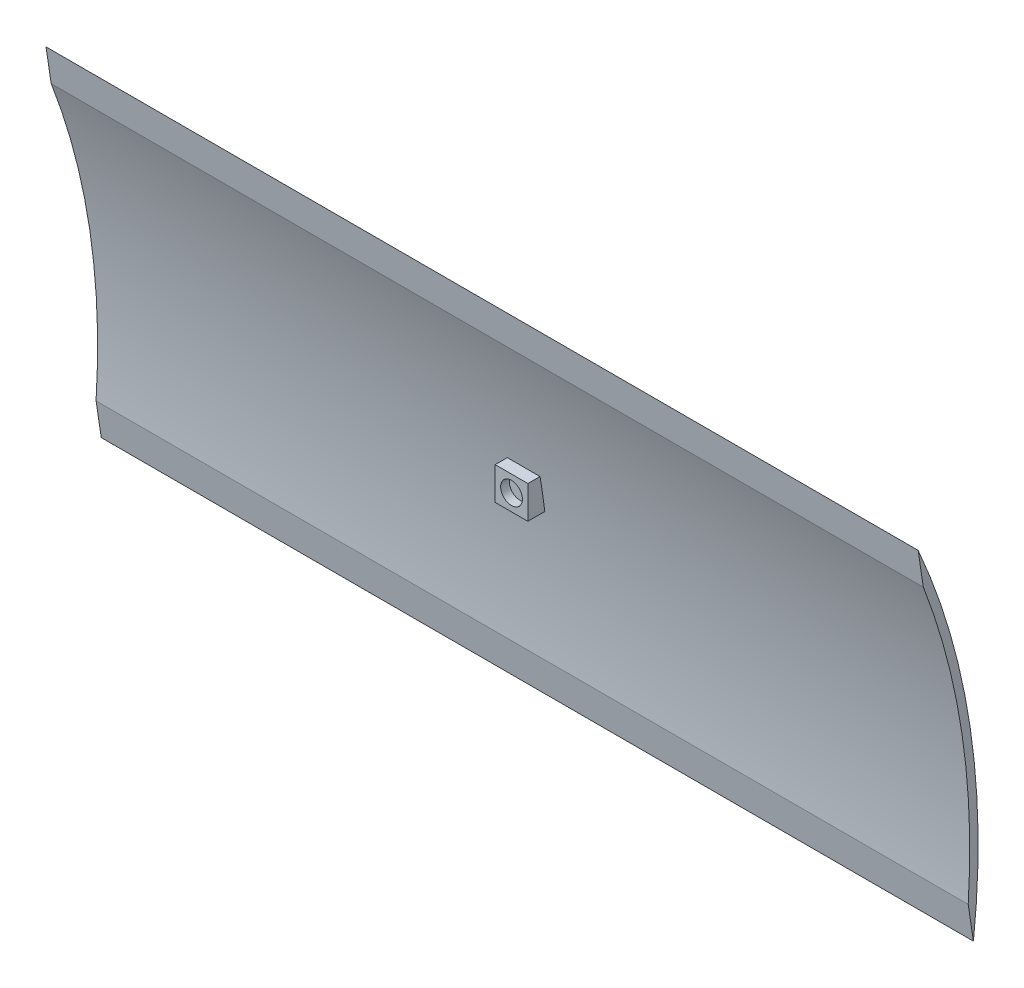
SolidWorks part; units mm, degrees
ref_plane "Front Plane" through (0, 0, 0) normal (0, 0, 1) x (1, 0, 0)
ref_plane "Top Plane" through (0, 0, 0) normal (0, 1, 0) x (1, 0, 0)
ref_plane "Right Plane" through (0, 0, 0) normal (1, 0, 0) x (0, 0, -1)
sketch "Sketch1" plane through (0, 0, 0) normal (1, 0, 0) x (0, 0, -1)
  line L0 (148.248, 65.3186) -> (149.4421, 57.4096)
  line L1 (159.7299, -10.7314) -> (160.924, -18.6404)
  arc A0 (159.7299, -10.7314) -> (149.4421, 57.4096) centre (0, 0) ccw
  arc A1 (160.924, -18.6404) -> (148.248, 65.3186) centre (0, 0) ccw
extrude "Boss-Extrude2" add sketch "Sketch1" along normal blind 150 and the other way blind 50
sketch "Sketch2" plane through (0, 0, 0) normal (0, 0, 1) x (1, 0, 0)
  line L0 (50, 57.4096) -> (50, -10.7314) construction
  line L1 (150, 57.4096) -> (-50, 57.4096) construction
  line L2 (150, -10.7314) -> (-50, -10.7314) construction
  line L3 (28.0596, 23.3391) -> (71.9404, 23.3391) construction
  line L5 (46.25, 27.0891) -> (53.75, 27.0891)
  line L6 (46.25, 27.0891) -> (46.25, 19.5891)
  line L7 (46.25, 19.5891) -> (53.75, 19.5891)
  line L8 (53.75, 27.0891) -> (53.75, 19.5891)
  line L9 (46.25, 27.0891) -> (53.75, 19.5891) construction
  line L10 (46.25, 19.5891) -> (53.75, 27.0891) construction
  point P6 (50, 23.3391)
  point P9 (50, 23.3391)
  dimension "D1" = 7.5
  dimension "D2" = 7.5
extrude "Boss-Extrude3" add sketch "Sketch2" against normal up to next from offset 155 offset against normal yes
sketch "Sketch3" plane through (0, 0, -155) normal (0, 0, 1) x (1, 0, 0)
  line L0 (50, 27.0891) -> (50, 19.5891) construction
  line L1 (53.75, 27.0891) -> (46.25, 27.0891) construction
  line L2 (46.25, 19.5891) -> (53.75, 19.5891) construction
  circle A0 centre (50, 23.3391) radius 2.5
extrude "Cut-Extrude1" cut sketch "Sketch3" against normal blind 2
